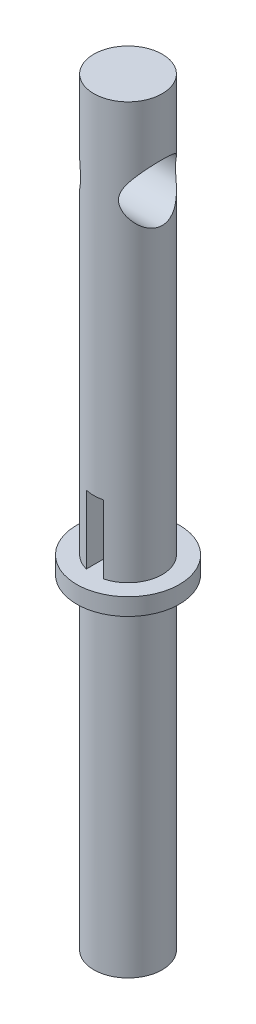
SolidWorks part; units mm, degrees
ref_plane "Front Plane" through (0, 0, 0) normal (0, 0, 1) x (1, 0, 0)
ref_plane "Top Plane" through (0, 0, 0) normal (0, 1, 0) x (1, 0, 0)
ref_plane "Right Plane" through (0, 0, 0) normal (1, 0, 0) x (0, 0, -1)
sketch "Sketch1" plane through (0, 0, 0) normal (0, 1, 0) x (1, 0, 0)
  circle A0 centre (0, 0) radius 6
extrude "Boss-Extrude1" add sketch "Sketch1" along normal blind 100
sketch "Sketch2" plane through (0, 0, 0) normal (0, 0, 1) x (1, 0, 0)
  line L0 (0, 100) -> (0, 60) construction
  line L1 (6, 100) -> (-6, 100) construction
  line L2 (0, 60) -> (0, 66)
  line L4 (-1.5, 60) -> (1.5, 60)
  line L5 (-1.5, 60) -> (-1.5, 72)
  line L6 (-1.5, 72) -> (1.5, 72)
  line L7 (1.5, 60) -> (1.5, 72)
  line L8 (-1.5, 60) -> (1.5, 72) construction
  line L9 (-1.5, 72) -> (1.5, 60) construction
  dimension "D1" = 12
  dimension "D2" = 3
extrude "Cut-Extrude2" cut sketch "Sketch2" against normal mid plane 100 contours L6 L7 L4 L5
sketch "Sketch3" plane through (0, 0, 0) normal (0, 0, 1) x (1, 0, 0)
  line L0 (0, 100) -> (0, 95)
  line L1 (6, 100) -> (-6, 100) construction
  circle A0 centre (0, 95) radius 2.5
extrude "Cut-Extrude3" cut sketch "Sketch3" against normal mid plane 100 contours A0
sketch "Sketch4" plane through (0, 0, 0) normal (0, -1, 0) x (1, 0, 0)
  circle A0 centre (0, 0) radius 9
extrude "Boss-Extrude2" add sketch "Sketch4" along normal blind 3 from offset 60 offset against normal yes
sketch "Sketch5" plane through (0, 100, 0) normal (0, 1, 0) x (1, 0, 0)
  circle A0 centre (0, 0) radius 6
extrude "Boss-Extrude3" add sketch "Sketch5" along normal mid plane 20
sketch "Sketch6" plane through (0, 0, 0) normal (0, 0, 1) x (1, 0, 0)
  line L0 (0, 110) -> (0, 105) construction
  line L1 (6, 110) -> (-6, 110) construction
  circle A0 centre (0, 105) radius 2.5
extrude "Cut-Extrude4" cut sketch "Sketch6" against normal mid plane 20
sketch "Sketch7" plane through (0, 110, 0) normal (0, 1, 0) x (1, 0, 0)
  circle A0 centre (0, 0) radius 6 construction
  circle A1 centre (0, 0) radius 6
extrude "Cut-Extrude5" cut sketch "Sketch7" against normal blind 12
sketch "Sketch8" plane through (0, 98, 0) normal (0, 1, 0) x (1, 0, 0)
  circle A0 centre (0, 0) radius 6 construction
  circle A1 centre (0, 0) radius 6
extrude "Boss-Extrude4" add sketch "Sketch8" along normal blind 30
sketch "Sketch10" plane through (0, 0, 0) normal (0, 0, 1) x (1, 0, 0)
  line L0 (0, 128) -> (0, 113)
  line L1 (6, 128) -> (-6, 128) construction
  circle A0 centre (0, 113) radius 5
extrude "Cut-Extrude6" cut sketch "Sketch10" against normal mid plane 60 contours A0
sketch "Sketch11" plane through (0, 128, 0) normal (0, 1, 0) x (1, 0, 0)
  circle A0 centre (0, 0) radius 6 construction
  circle A1 centre (0, 0) radius 6
extrude "Boss-Extrude5" add sketch "Sketch11" against normal blind 40
sketch "Sketch12" plane through (0, 128, 0) normal (0, 1, 0) x (1, 0, 0)
  circle A0 centre (0, 0) radius 6 construction
  circle A1 centre (0, 0) radius 6
extrude "Boss-Extrude6" add sketch "Sketch12" along normal blind 5
sketch "Sketch13" plane through (0, 0, 0) normal (1, 0, 0) x (0, 0, -1)
  line L0 (0, 133) -> (0, 118)
  line L1 (6, 133) -> (-6, 133) construction
  circle A0 centre (0, 118) radius 5
extrude "Cut-Extrude7" cut sketch "Sketch13" against normal mid plane 55 contours A0
